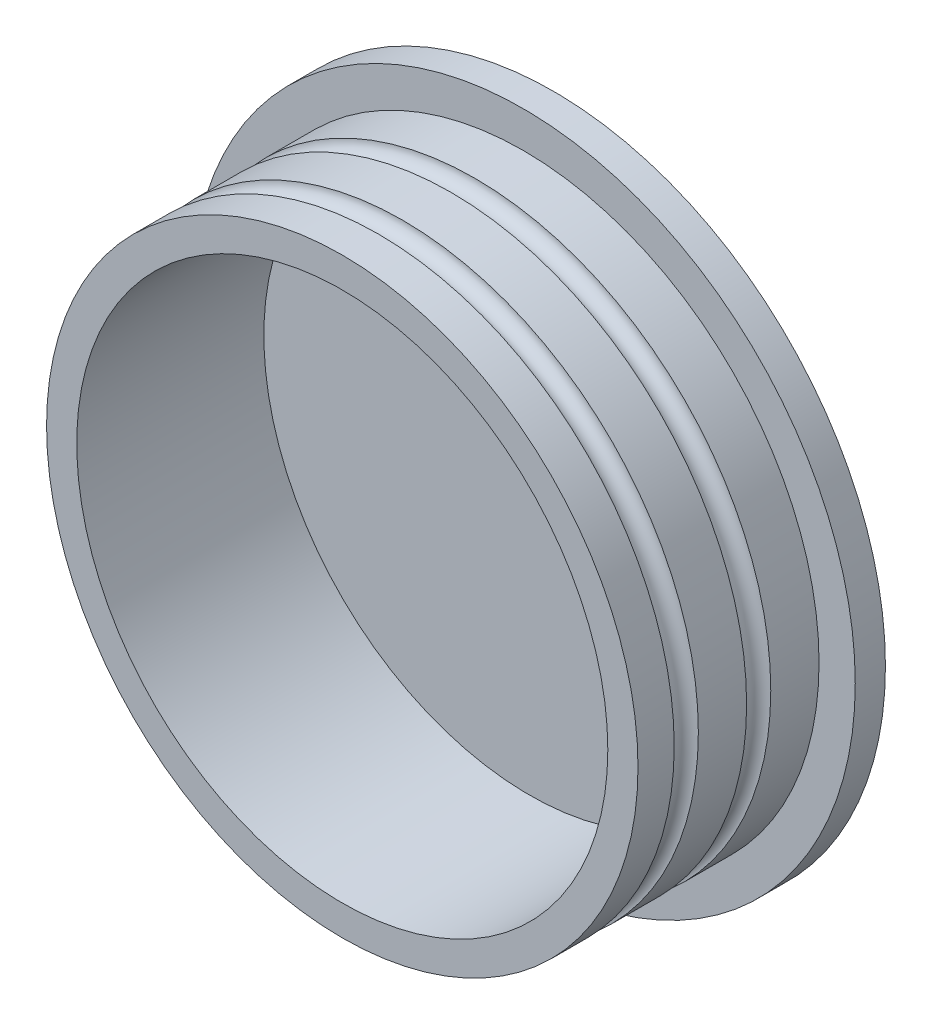
SolidWorks part; units mm, degrees
material "PVC 0.007 Plastificado"
ref_plane "Alzado" through (0, 0, 0) normal (0, 0, 1) x (1, 0, 0)
ref_plane "Planta" through (0, 0, 0) normal (0, 1, 0) x (1, 0, 0)
ref_plane "Vista lateral" through (0, 0, 0) normal (1, 0, 0) x (0, 0, -1)
sketch "Croquis1" plane through (0, 0, 0) normal (0, 0, 1) x (1, 0, 0)
  circle A0 centre (0, 0) radius 55
  dimension "D1" = 110
extrude "Saliente-Extruir1" add sketch "Croquis1" along normal blind 5
sketch "Croquis2" plane through (0, 0, 5) normal (0, 0, 1) x (1, 0, 0)
  circle A0 centre (0, 0) radius 49
  dimension "D1" = 98
extrude "Saliente-Extruir2" add sketch "Croquis2" along normal blind 30
sketch "Croquis3" plane through (0, 0, 0) normal (0, 1, 0) x (1, 0, 0)
  line L0 (-49, -5) -> (-49, -35) construction
  line L1 (-49, -5) -> (49, -5) construction
  line L2 (-49, -35) -> (49, -35) construction
  circle A0 centre (-49, -15) radius 2
  circle A2 centre (-49, -27) radius 2
  dimension "D1" = 4
  dimension "D2" = 10
  dimension "D3" = 8
sketch "Rev axis" plane through (0, 0, 0) normal (0, 1, 0) x (1, 0, 0)
  line L0 (0, -36.878) -> (0, 0) construction
revolve "Cortar-Revolución1" cut sketch "Croquis3" angle 360 about L0
sketch "Croquis4" plane through (0, 0, 35) normal (0, 0, 1) x (1, 0, 0)
  circle A0 centre (0, 0) radius 44
  circle A1 centre (0, 0) radius 49 construction
  dimension "D1" = 5
extrude "Cortar-Extruir1" cut sketch "Croquis4" against normal offset from surface (31 mm away) 4 up to face at (55, 0, 0)
sketch "Croquis5" plane through (0, 0, 0) normal (0, 0, -1) x (-1, 0, 0)
  circle A0 centre (0, 0) radius 27.5
  circle A1 centre (0, 0) radius 55 construction
  point P0 (0, 27.5)
  point P12 (23.8157, 13.75)
  point P13 (23.8157, -13.75)
  point P14 (0, -27.5)
  point P17 (-23.8157, -13.75)
  point P18 (-23.8157, 13.75)
  point P19 (0, 0)
  dimension "D1" = 55
  dimension "D2" = 6
sketch "Croquis12" [suppressed] plane through (0, 0, 0) normal (0, 0, -1) x (-1, 0, 0)
  circle A0 centre (0, 0) radius 44
  circle A2 centre (0, 0) radius 49 construction
  dimension "D1" = 5
extrude "Cortar-Extruir2" [suppressed] cut sketch "Croquis12" against normal through all both and the other way through all
sketch "Croquis13" [suppressed] plane through (0, 0, 35) normal (0, 0, 1) x (1, 0, 0)
  line L0 (0, 0) -> (0, -65.343) construction
  line L1 (-6, -47.589) -> (6, -47.589)
  line L2 (6, -47.589) -> (6, -43.589)
  line L3 (0, -47.589) -> (0, -44)
  line L4 (-6, -47.589) -> (-6, -43.589)
  circle A0 centre (0, 0) radius 44 construction
  arc A1 (-6, -43.589) -> (6, -43.589) centre (0, 0) ccw
  circle M6 centre (0, 0) radius 44
  dimension "D1" = 6
  dimension "D2" = 4
extrude "Cortar-Extruir3" [suppressed] cut sketch "Croquis13" against normal blind 6 contours L4 L1 L3 M6 | L3 L1 L2 M6
